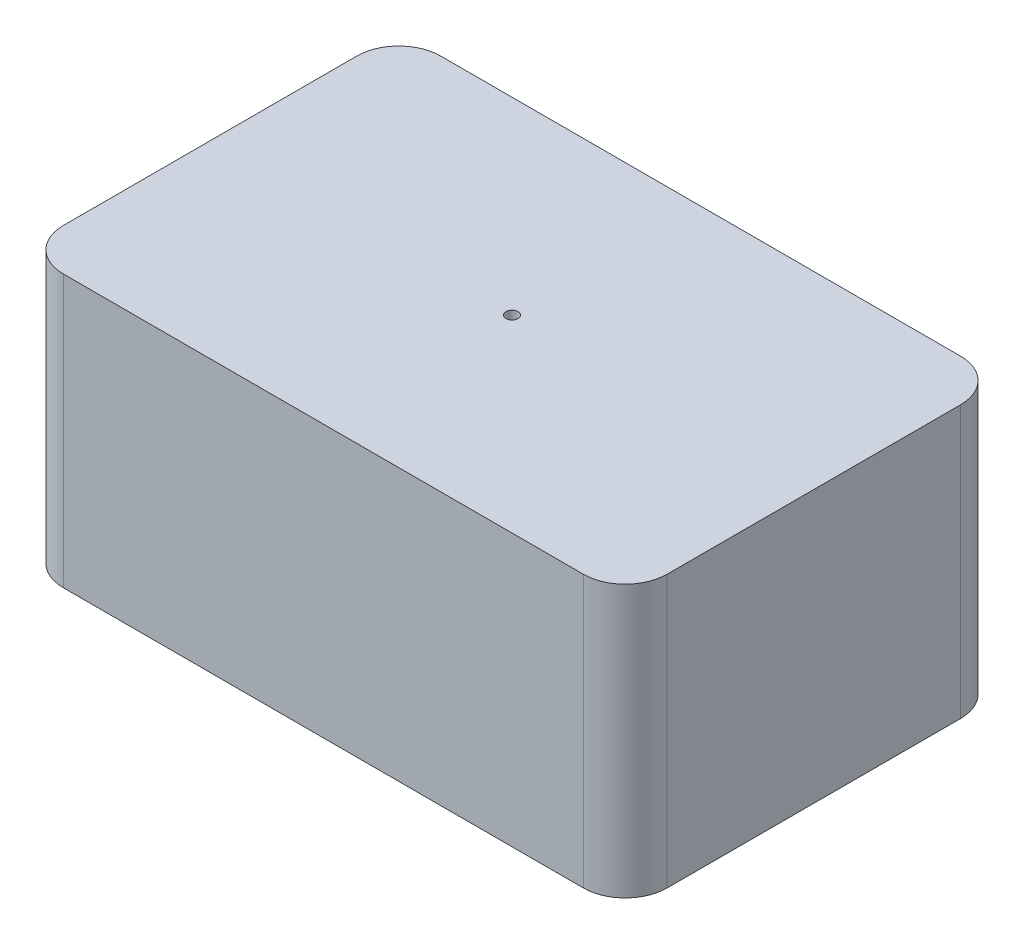
SolidWorks part; units mm, degrees
ref_plane "Front Plane" through (0, 0, 0) normal (0, 0, 1) x (1, 0, 0)
ref_plane "Top Plane" through (0, 0, 0) normal (0, 1, 0) x (1, 0, 0)
ref_plane "Right Plane" through (0, 0, 0) normal (1, 0, 0) x (0, 0, -1)
sketch "Sketch2" plane through (0, 0, 0) normal (0, 1, 0) x (1, 0, 0)
  line L0 (0, 0) -> (0.4, 0) construction
  line L1 (0, 12.5) -> (0, -12.5) construction
  line L2 (-20, 9.7232) -> (-20, -9.7232)
  line L3 (-17.2232, 12.5) -> (17.2232, 12.5)
  line L4 (20, 9.7232) -> (20, -9.7232)
  line L5 (17.2232, -12.5) -> (-17.2232, -12.5)
  line L6 (-20, 0) -> (20, 0) construction
  circle A0 centre (0, 0) radius 0.4
  arc A1 (-17.2232, 12.5) -> (-20, 9.7232) centre (-17.2232, 9.7232) ccw
  arc A2 (-17.2232, -12.5) -> (-20, -9.7232) centre (-17.2232, -9.7232) cw
  arc A3 (17.2232, -12.5) -> (20, -9.7232) centre (17.2232, -9.7232) ccw
  arc A4 (17.2232, 12.5) -> (20, 9.7232) centre (17.2232, 9.7232) cw
  point P9 (-20, 0)
  dimension "D1" = 0.4
  dimension "D4" = 40
  dimension "D5" = 25
extrude "Boss-Extrude1" add sketch "Sketch2" along normal blind 18
sketch "Sketch3" plane through (0, 0, 0) normal (0, -1, 0) x (1, 0, 0)
  line L12 (19, -9.7232) -> (19, 9.7232)
  line L13 (17.2232, 11.5) -> (-17.2232, 11.5)
  line L14 (-19, 9.7232) -> (-19, -9.7232)
  line L15 (-17.2232, -11.5) -> (17.2232, -11.5)
  line L16 (19, -9.7232) -> (19, 9.7232)
  line L17 (17.2232, 11.5) -> (-17.2232, 11.5)
  line L18 (-19, 9.7232) -> (-19, -9.7232)
  line L19 (-17.2232, -11.5) -> (17.2232, -11.5)
  arc A12 (17.2232, -11.5) -> (19, -9.7232) centre (17.2232, -9.7232) ccw
  arc A13 (19, 9.7232) -> (17.2232, 11.5) centre (17.2232, 9.7232) ccw
  arc A14 (-17.2232, 11.5) -> (-19, 9.7232) centre (-17.2232, 9.7232) ccw
  arc A15 (-19, -9.7232) -> (-17.2232, -11.5) centre (-17.2232, -9.7232) ccw
  arc A16 (17.2232, -11.5) -> (19, -9.7232) centre (17.2232, -9.7232) ccw
  arc A17 (19, 9.7232) -> (17.2232, 11.5) centre (17.2232, 9.7232) ccw
  arc A18 (-17.2232, 11.5) -> (-19, 9.7232) centre (-17.2232, 9.7232) ccw
  arc A19 (-19, -9.7232) -> (-17.2232, -11.5) centre (-17.2232, -9.7232) ccw
  dimension "D1" = 1
extrude "Cut-Extrude1" cut sketch "Sketch3" against normal blind 17 contours A16 L16 A17 L17 A18 L18 A19 L19
